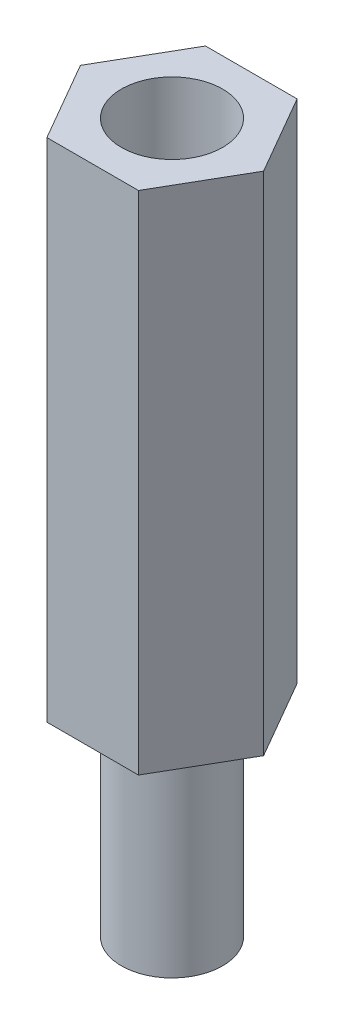
SolidWorks part; units mm, degrees
material "黄铜"
ref_plane "前视基准面" through (0, 0, 0) normal (0, 0, 1) x (1, 0, 0)
ref_plane "上视基准面" through (0, 0, 0) normal (0, 1, 0) x (1, 0, 0)
ref_plane "右视基准面" through (0, 0, 0) normal (1, 0, 0) x (0, 0, -1)
sketch "草图1" plane through (0, 0, 0) normal (0, 1, 0) x (1, 0, 0)
  line L1 (2.7135, 0) -> (1.3568, 2.35)
  line L2 (1.3568, 2.35) -> (-1.3568, 2.35)
  line L3 (-1.3568, 2.35) -> (-2.7135, 0)
  line L4 (-2.7135, 0) -> (-1.3568, -2.35)
  line L5 (-1.3568, -2.35) -> (1.3568, -2.35)
  line L6 (1.3568, -2.35) -> (2.7135, 0)
  circle A0 centre (0, 0) radius 1.5
  circle A1 centre (0, 0) radius 2.35 construction
  dimension "D1" = 3
  dimension "D2" = 4.7
extrude "凸台-拉伸1" add sketch "草图1" along normal blind 15
sketch "草图2" plane through (0, 0, 0) normal (0, -1, 0) x (-1, 0, 0)
  circle A0 centre (0, 0) radius 1.5
extrude "凸台-拉伸2" add sketch "草图2" along normal blind 6 separate body
